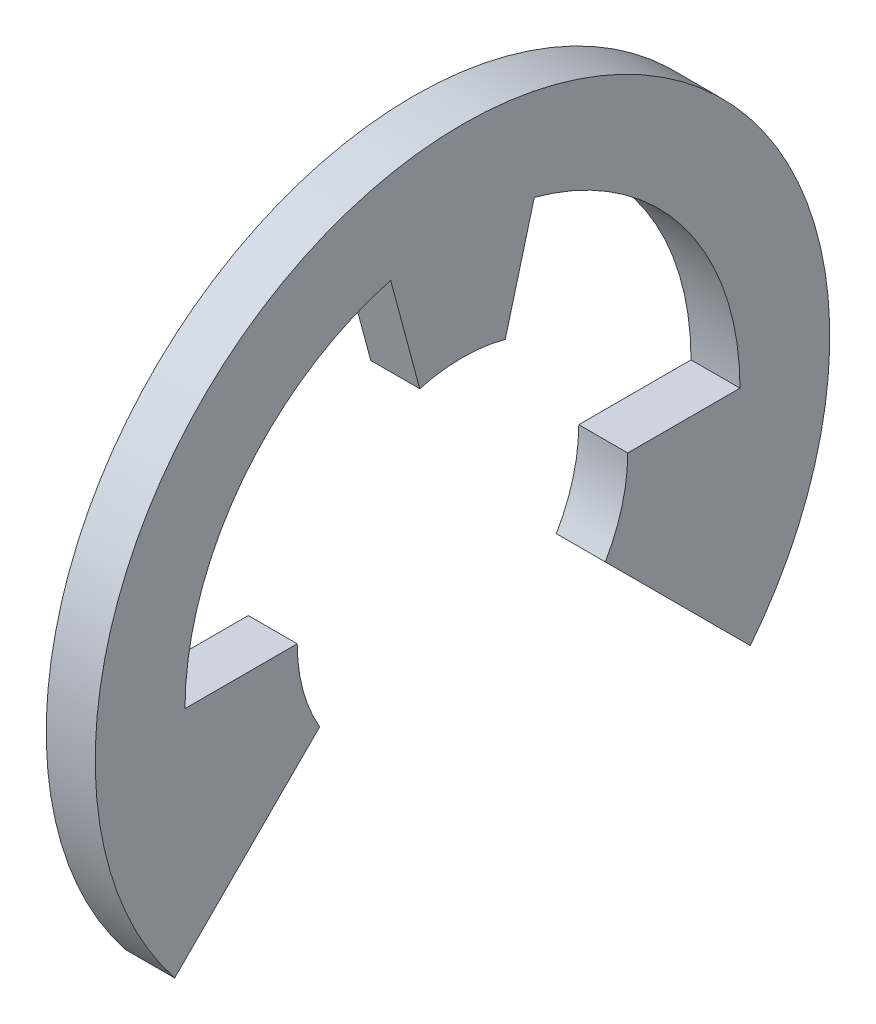
SolidWorks part; units mm, degrees
ref_plane "Front Plane" through (0, 0, 0) normal (0, 0, 1) x (1, 0, 0)
ref_plane "Top Plane" through (0, 0, 0) normal (0, 1, 0) x (1, 0, 0)
ref_plane "Right Plane" through (0, 0, 0) normal (1, 0, 0) x (0, 0, -1)
sketch "Sketch1" plane through (0, 0, 0) normal (1, 0, 0) x (0, 0, -1)
  line L0 (-2.025, 0) -> (-3.4, 0)
  line L1 (-0.5241, 1.956) -> (-0.88, 3.2841)
  line L2 (2.025, 0) -> (3.4, 0)
  line L3 (0.88, 3.2841) -> (0.5241, 1.956)
  line L4 (-1.75, -1.0189) -> (-3.5265, -2.7954)
  line L5 (1.75, -1.0189) -> (3.5265, -2.7954)
  line L9 (0, 0) -> (0, 4.5) construction
  arc A0 (-2.025, 0) -> (-1.75, -1.0189) centre (0, 0) ccw
  arc A1 (3.5265, -2.7954) -> (-3.5265, -2.7954) centre (0, 0) ccw
  arc A2 (3.4, 0) -> (0.88, 3.2841) centre (0, 0) ccw
  arc A3 (0.5241, 1.956) -> (-0.5241, 1.956) centre (0, 0) ccw
  arc A4 (-0.88, 3.2841) -> (-3.4, 0) centre (0, 0) ccw
  arc A5 (1.75, -1.0189) -> (2.025, 0) centre (0, 0) ccw
  circle A6 centre (0, 0) radius 2.025 construction
  dimension "D1" = 30
  dimension "D2" = 90
  dimension "REE_D" = 9
  dimension "REE_D_s" = 4.05
  dimension "REE_B_s" = 1.1
  dimension "REE_H" = 3.5
extrude "Boss-Extrude1" add sketch "Sketch1" along normal blind 0.6
